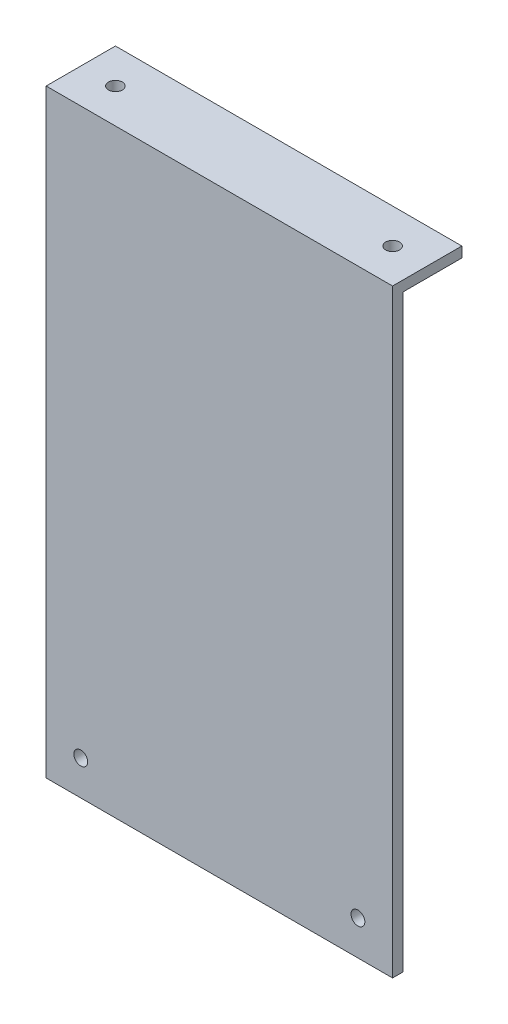
SolidWorks part; units mm, degrees
ref_plane "Front Plane" through (0, 0, 0) normal (0, 0, 1) x (1, 0, 0)
ref_plane "Top Plane" through (0, 0, 0) normal (0, 1, 0) x (1, 0, 0)
ref_plane "Right Plane" through (0, 0, 0) normal (1, 0, 0) x (0, 0, -1)
sketch "Sketch1" plane through (0, 0, 0) normal (0, 1, 0) x (1, 0, 0)
  line L1 (-50, -10) -> (50, -10)
  line L2 (-50, -10) -> (-50, 10)
  line L3 (-50, 10) -> (50, 10)
  line L4 (50, -10) -> (50, 10)
  line L5 (-50, -10) -> (50, 10) construction
  line L6 (-50, 10) -> (50, -10) construction
  point P0 (0, 0)
  dimension "D1" = 100
  dimension "D2" = 20
extrude "Boss-Extrude1" add sketch "Sketch1" along normal blind 3
sketch "Sketch2" plane through (0, 3, 0) normal (0, 1, 0) x (1, 0, 0)
  line L0 (50, -10) -> (50, 10) construction
  line L1 (-50, -10) -> (50, -10) construction
  line L2 (-50, 10) -> (-50, -10) construction
  circle A0 centre (40, 0) radius 2
  circle A1 centre (-40, 0) radius 2
  point P4 (0, 0)
  dimension "D1" = 4
  dimension "D2" = 4
  dimension "D3" = 10
  dimension "D4" = 10
  dimension "D5" = 10
extrude "Cut-Extrude1" cut sketch "Sketch2" against normal up to next
sketch "Sketch3" plane through (0, 0, 0) normal (0, -1, 0) x (1, 0, 0)
  line L0 (50, 10) -> (50, -10) construction
  line L1 (-50, 10) -> (50, 10)
  line L2 (-50, 10) -> (-50, 7)
  line L3 (-50, 7) -> (50, 7)
  line L4 (50, 10) -> (50, 7)
  dimension "D1" = 3
extrude "Boss-Extrude2" add sketch "Sketch3" along normal blind 170
sketch "Sketch4" plane through (0, 0, 10) normal (0, 0, 1) x (1, 0, 0)
  line L0 (-50, 3) -> (-50, -170) construction
  line L1 (50, -170) -> (-50, -170) construction
  line L2 (50, 3) -> (50, -170) construction
  circle A0 centre (-40, -160) radius 2
  circle A1 centre (40, -160) radius 2
  point P4 (0, 0)
  dimension "D1" = 4
  dimension "D2" = 4
  dimension "D3" = 10
  dimension "D4" = 10
  dimension "D5" = 10
extrude "Cut-Extrude2" cut sketch "Sketch4" against normal up to next
